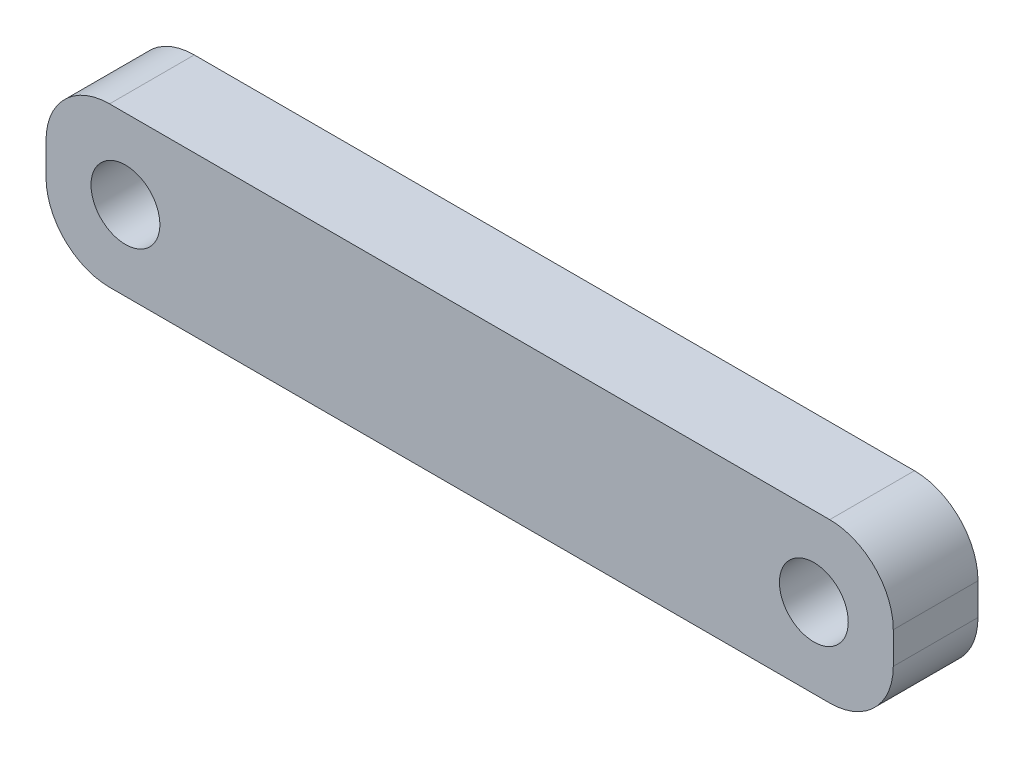
SolidWorks part; units mm, degrees
ref_plane "Front Plane" through (0, 0, 0) normal (0, 0, 1) x (1, 0, 0)
ref_plane "Top Plane" through (0, 0, 0) normal (0, 1, 0) x (1, 0, 0)
ref_plane "Right Plane" through (0, 0, 0) normal (1, 0, 0) x (0, 0, -1)
sketch "Sketch2" plane through (0, 0, 0) normal (0, 0, 1) x (1, 0, 0)
  line L0 (0, 0) -> (20, 0)
  line L1 (20, 0) -> (20, 7.5)
  line L2 (20, 7.5) -> (-20, 7.5)
  line L3 (-20, 7.5) -> (-20, 0)
  line L4 (-20, 0) -> (0, 0)
  line L5 (0, 0) -> (0, 7.5) construction
  line L6 (0, 3.75) -> (20, 3.75) construction
  circle A0 centre (16.25, 3.75) radius 1.625
  circle A1 centre (-16.25, 3.75) radius 1.625
  point P11 (16.2756, 3.75)
  dimension "D3" = 3.25
  dimension "D4" = 3.75
  dimension "D1" = 40
  dimension "D2" = 7.5
extrude "Boss-Extrude1" add sketch "Sketch2" along normal blind 4
fillet "Fillet1" radius 3 4 edges at (20, 0, 2) (20, 7.5, 2) (-20, 0, 2) (-20, 7.5, 2)
